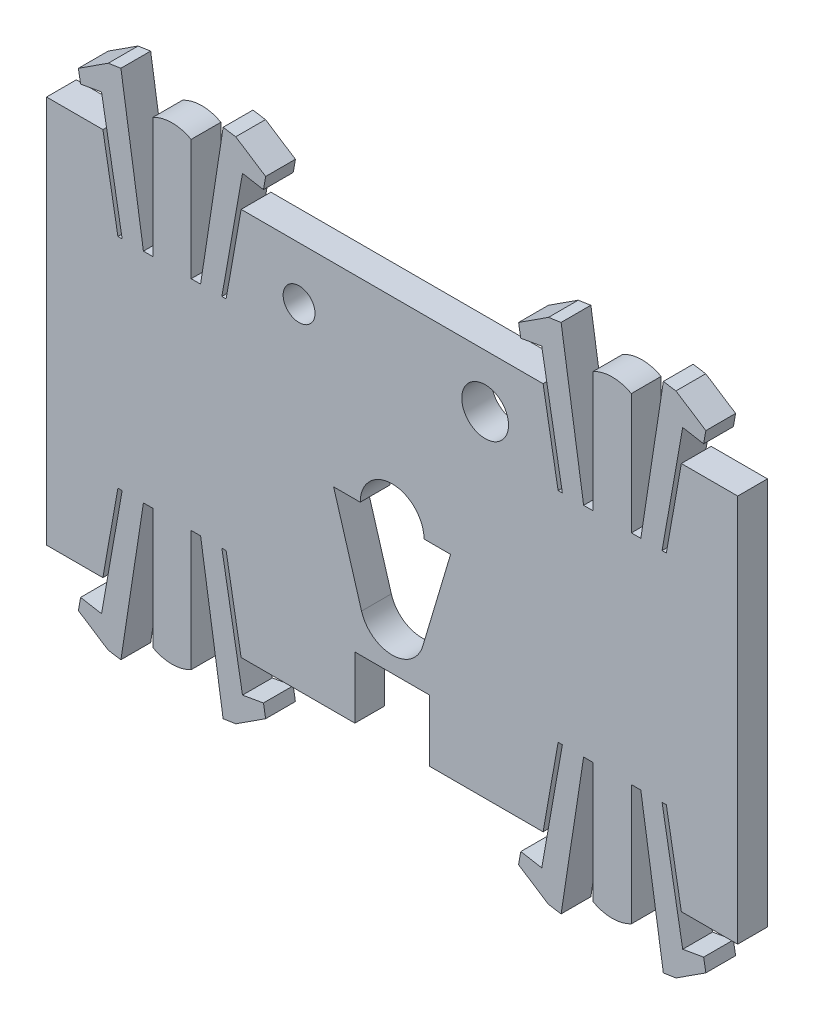
SolidWorks part; units mm, degrees
ref_plane "Přední rovina" through (0, 0, 0) normal (0, 0, 1) x (1, 0, 0)
ref_plane "Horní rovina" through (0, 0, 0) normal (0, 1, 0) x (1, 0, 0)
ref_plane "Pravá rovina" through (0, 0, 0) normal (1, 0, 0) x (0, 0, -1)
sketch "Model" plane through (0, 0, 0) normal (0, 0, 1) x (1, 0, 0)
  line L0 (-999.9987, 24.25) -> (49000.0013, 24.25) construction
  line L1 (-14.2, 18.25) -> (14.2, 18.25)
  line L2 (-27.2, -981.75) -> (-27.2, 49018.25) construction
  line L3 (-14.2, -981.75) -> (-14.2, 49018.25) construction
  line L4 (-20.7, -976.145) -> (-20.7, 49023.855) construction
  line L5 (32.5, 18.25) -> (27.2, 18.25)
  line L6 (25.7894, 10.25) -> (25.3894, 10.25)
  line L7 (25.7894, 10.25) -> (27.2, 18.25)
  line L8 (27.329, 21.25) -> (25.3894, 10.25)
  line L9 (29.2986, 20.9027) -> (27.329, 21.25)
  line L10 (29.2986, 20.9027) -> (29.507, 22.0845)
  line L11 (26.6932, 23.9074) -> (29.507, 22.0845)
  line L12 (25.507, 24.0889) -> (26.6932, 23.9074)
  line L13 (23.3894, 10.25) -> (25.507, 24.0889)
  line L19 (18.0106, 10.25) -> (15.893, 24.0889)
  line L20 (15.893, 24.0889) -> (14.7068, 23.9074)
  line L21 (14.7068, 23.9074) -> (11.893, 22.0845)
  line L25 (-1000, 10.25) -> (49000, 10.25) construction
  line L28 (-25.7894, 10.25) -> (-25.3894, 10.25)
  line L29 (-29.2986, 20.9027) -> (-29.507, 22.0845)
  line L30 (-25.507, 24.0889) -> (-26.6932, 23.9074)
  line L32 (-15.893, 24.0889) -> (-14.7068, 23.9074)
  line L33 (-14.7068, 23.9074) -> (-11.893, 22.0845)
  line L34 (-23.3894, 10.25) -> (-25.507, 24.0889)
  line L35 (-26.6932, 23.9074) -> (-29.507, 22.0845)
  line L36 (-29.2986, 20.9027) -> (-27.329, 21.25)
  line L37 (-27.329, 21.25) -> (-25.3894, 10.25)
  line L38 (-25.7894, 10.25) -> (-27.2, 18.25)
  line L39 (-27.2, 18.25) -> (-32.5, 18.25)
  line L40 (-12.1014, 20.9027) -> (-11.893, 22.0845)
  line L41 (-32.5, -18.25) -> (-32.5, 18.25)
  line L42 (32.5, -18.25) -> (32.5, 18.25)
  line L43 (-3.5, -12.45) -> (3.5, -12.45)
  line L44 (-27.2, -18.25) -> (-32.5, -18.25)
  line L45 (0, -7.95) -> (-2.875, -8.8069) construction
  line L46 (2.875, -8.8069) -> (5.5, 0)
  line L47 (5.5, 0) -> (3, 0)
  line L48 (-15.6106, -10.25) -> (-14.2, -18.25)
  line L49 (-15.6106, -10.25) -> (-16.0106, -10.25)
  line L50 (-14.071, -21.25) -> (-16.0106, -10.25)
  line L51 (-12.1014, -20.9027) -> (-14.071, -21.25)
  line L52 (-12.1014, -20.9027) -> (-11.893, -22.0845)
  line L53 (-14.7068, -23.9074) -> (-11.893, -22.0845)
  line L54 (-15.893, -24.0889) -> (-14.7068, -23.9074)
  line L56 (-18.0106, -10.25) -> (-15.893, -24.0889)
  line L58 (-14.2, -18.25) -> (-3.5, -18.25)
  line L59 (-3.5, -18.25) -> (-3.5, -12.45)
  line L63 (-23.3894, -10.25) -> (-25.507, -24.0889)
  line L64 (-25.507, -24.0889) -> (-26.6932, -23.9074)
  line L65 (-29.2986, -20.9027) -> (-29.507, -22.0845)
  line L66 (-26.6932, -23.9074) -> (-29.507, -22.0845)
  line L67 (-29.2986, -20.9027) -> (-27.329, -21.25)
  line L68 (-27.329, -21.25) -> (-25.3894, -10.25)
  line L69 (-25.7894, -10.25) -> (-27.2, -18.25)
  line L70 (-25.7894, -10.25) -> (-25.3894, -10.25)
  line L71 (27.2, -18.25) -> (32.5, -18.25)
  line L72 (25.7894, -10.25) -> (27.2, -18.25)
  line L73 (25.7894, -10.25) -> (25.3894, -10.25)
  line L74 (27.329, -21.25) -> (25.3894, -10.25)
  line L75 (29.2986, -20.9027) -> (27.329, -21.25)
  line L76 (29.2986, -20.9027) -> (29.507, -22.0845)
  line L77 (26.6932, -23.9074) -> (29.507, -22.0845)
  line L78 (25.507, -24.0889) -> (26.6932, -23.9074)
  line L79 (23.3894, -10.25) -> (25.507, -24.0889)
  line L81 (-2.875, -8.8069) -> (-5.5, 0)
  line L82 (-5.5, 0) -> (-3, 0)
  line L84 (0, -1000) -> (0, 49000) construction
  line L85 (-1000, 0) -> (49000, 0) construction
  line L86 (-12.1014, 20.9027) -> (-14.071, 21.25)
  line L87 (32.5, 18.25) -> (-32.5, 18.25) construction
  line L88 (32.5, 18.25) -> (32.5, -18.25) construction
  line L89 (32.5, -18.25) -> (-32.5, -18.25) construction
  line L90 (-32.5, 18.25) -> (-32.5, -18.25) construction
  line L91 (32.5, 18.25) -> (-32.5, -18.25) construction
  line L92 (32.5, -18.25) -> (-32.5, 18.25) construction
  line L95 (-18.0106, 10.25) -> (-15.893, 24.0889)
  line L96 (-14.071, 21.25) -> (-16.0106, 10.25)
  line L97 (-15.6106, 10.25) -> (-16.0106, 10.25)
  line L98 (-15.6106, 10.25) -> (-14.2, 18.25)
  line L99 (12.1014, 20.9027) -> (11.893, 22.0845)
  line L100 (12.1014, 20.9027) -> (14.071, 21.25)
  line L101 (14.071, 21.25) -> (16.0106, 10.25)
  line L102 (15.6106, 10.25) -> (16.0106, 10.25)
  line L103 (15.6106, 10.25) -> (14.2, 18.25)
  line L107 (18.0106, -10.25) -> (15.893, -24.0889)
  line L108 (15.893, -24.0889) -> (14.7068, -23.9074)
  line L109 (12.1014, -20.9027) -> (11.893, -22.0845)
  line L110 (14.7068, -23.9074) -> (11.893, -22.0845)
  line L111 (12.1014, -20.9027) -> (14.071, -21.25)
  line L112 (14.071, -21.25) -> (16.0106, -10.25)
  line L113 (15.6106, -10.25) -> (16.0106, -10.25)
  line L114 (15.6106, -10.25) -> (14.2, -18.25)
  line L115 (14.2, -18.25) -> (3.5, -18.25)
  line L116 (3.5, -18.25) -> (3.5, -12.45)
  line L121 (-22.5, 10.25) -> (-22.5, 21.5966)
  line L123 (-18.9, 10.25) -> (-18.9, 21.5966)
  line L128 (22.5, 10.25) -> (22.5, 21.5966)
  line L129 (18.9, 10.25) -> (18.9, 21.5966)
  line L132 (22.5, -10.25) -> (22.5, -21.5966)
  line L135 (18.9, -10.25) -> (18.9, -21.5966)
  line L138 (-18.9, -10.25) -> (-18.9, -21.5966)
  line L141 (-22.5, -10.25) -> (-22.5, -21.5966)
  line L142 (-22.5, 10.25) -> (-23.3894, 10.25)
  line L143 (-18.9, 10.25) -> (-18.0106, 10.25)
  line L144 (18.9, 10.25) -> (18.0106, 10.25)
  line L145 (22.5, 10.25) -> (23.3894, 10.25)
  line L146 (22.5, -10.25) -> (23.3894, -10.25)
  line L147 (18.9, -10.25) -> (18.0106, -10.25)
  line L148 (-18.9, -10.25) -> (-18.0106, -10.25)
  line L149 (-22.5, -10.25) -> (-23.3894, -10.25)
  line L150 (-10.6253, 11.75) -> (-7.157, 11.75) construction
  circle A0 centre (-8.75, 13.25) radius 1.5
  circle A1 centre (8.75, 13.25) radius 2.2
  circle A2 centre (0, -7.95) radius 3 construction
  circle A4 centre (0, 0) radius 3 construction
  arc A5 (-3, 0) -> (3, 0) centre (0, 0) cw
  arc A6 (-2.875, -8.8069) -> (2.875, -8.8069) centre (0, -7.95) ccw
  arc A7 (-24.5, 18.25) -> (-16.9, 18.25) centre (-20.7, 18.25) cw construction
  arc A12 (22.5, 21.5966) -> (18.9, 21.5966) centre (20.7, 18.25) ccw
  arc A15 (22.5, -21.5966) -> (18.9, -21.5966) centre (20.7, -18.25) cw
  arc A18 (-22.5, -21.5966) -> (-18.9, -21.5966) centre (-20.7, -18.25) ccw
  arc A19 (-22.5, 21.5966) -> (-18.9, 21.5966) centre (-20.7, 18.25) cw
  point P1 (0, 18.25)
  point P104 (0, -12.45)
  point P268 (0, 0)
  dimension "D17" = 30
  dimension "D19" = 3
  dimension "D22" = 4.5
  dimension "D23" = 6
  dimension "D24" = 6
  dimension "D25" = 4.4
  dimension "D26" = 1.8
  dimension "D14" = 3.8
  dimension "D27" = 5.5
  dimension "D1" = 65
  dimension "D2" = 36.5
  dimension "D3" = 6
  dimension "D4" = 13
  dimension "D5" = 14.2
  dimension "D6" = 0.4
  dimension "D7" = 8
  dimension "D8" = 2
  dimension "D9" = 80
  dimension "D10" = 2
  dimension "D11" = 3
  dimension "D12" = 2.6527
  dimension "D13" = 1.2
  dimension "D15" = 1.2
  dimension "D16" = 14
  dimension "D18" = 8.75
  dimension "D20" = 3.5
  dimension "D21" = 5.8
  dimension "D29" = 81.3
extrude "Přidat vysunutím1" add sketch "Model" along normal blind 2.8
